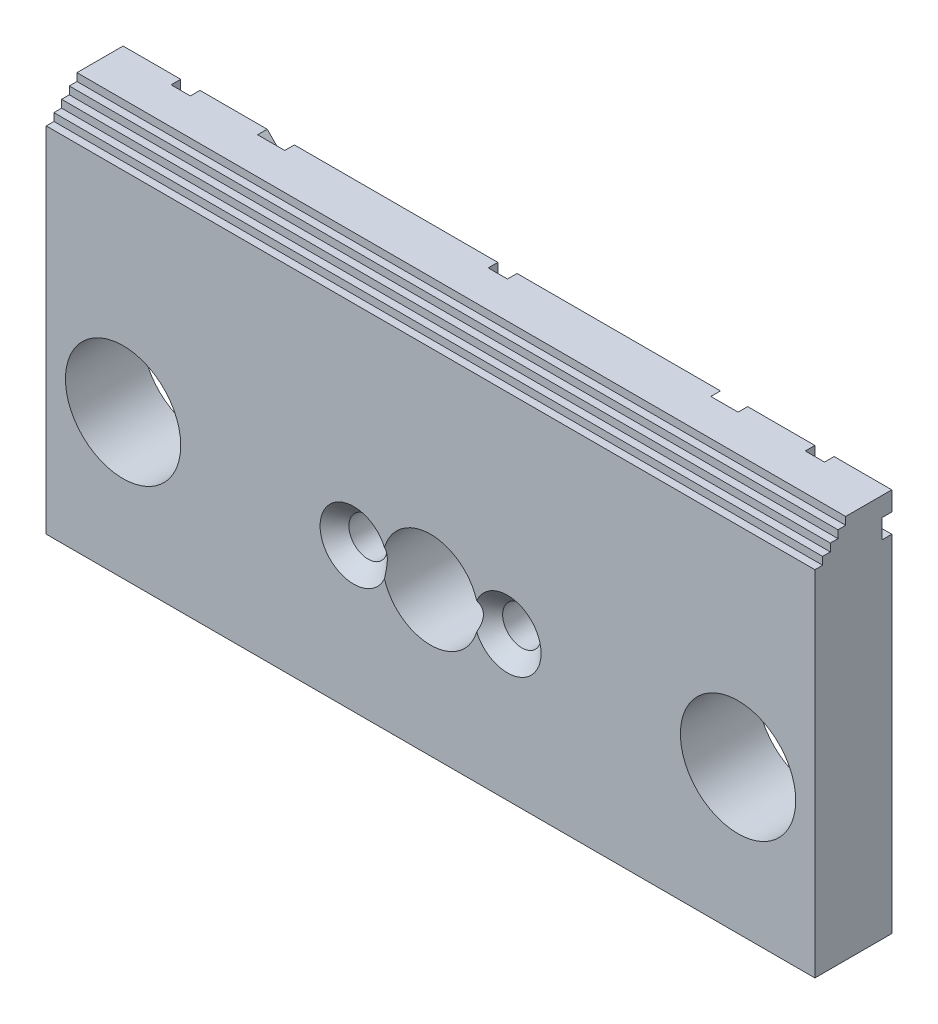
SolidWorks part; units mm, degrees
ref_plane "前视基准面" through (0, 0, 0) normal (0, 0, 1) x (1, 0, 0)
ref_plane "上视基准面" through (0, 0, 0) normal (0, 1, 0) x (1, 0, 0)
ref_plane "右视基准面" through (0, 0, 0) normal (1, 0, 0) x (0, 0, -1)
other "Configuration Table"
ref_plane "基准面1" through (0, 0, 1) normal (0, 0, -1) x (-1, 0, 0)
sketch "草图1" plane through (0, 0, 1) normal (0, 0, -1) x (-1, 0, 0)
  line L0 (-80, -13.3333) -> (0, -13.3333)
  line L1 (0, -13.3333) -> (0, 46.6667)
  line L2 (0, 46.6667) -> (-80, 46.6667)
  line L3 (-80, 46.6667) -> (-80, -13.3333)
  dimension "D1" = 80
  dimension "D2" = 60
extrude "凸台-拉伸1" add sketch "草图1" against normal blind 8
hole_wizard "Ø12.0 (12) 直径孔1" positions "草图21" profile "草图20" hole size "Ø12.0" standard "ANSI Metric" end condition through all
sketch "草图21" plane through (0, 0, 9) normal (0, 0, 1) x (1, 0, 0)
  line L0 (80, 21.6667) -> (0, 21.6667) construction
  line L1 (80, 46.6667) -> (80, -13.3333) construction
  line L2 (0, -13.3333) -> (0, 46.6667) construction
  line L3 (0, 46.6667) -> (80, 46.6667) construction
  point P0 (72, 21.6667)
  point P1 (8, 21.6667)
  dimension "D1" = 8
  dimension "D2" = 8
  dimension "D3" = 25
sketch "草图20" plane through (72, 21.6667, 9) normal (1, 0, 0) x (0, -1, 0)
  line L0 (0, 0) -> (0, 8)
  line L1 (0, 8) -> (6, 8)
  line L2 (6, 8) -> (6, 0)
  line L5 (6, 0) -> (0, 0)
  line L11 (0, -6.35) -> (0, 107.95) construction
  dimension "通孔孔直径" = 12
  dimension "通孔孔深度" = 8
hole_wizard "Ø10.0 (10) 直径孔2" positions "草图23" profile "草图22" hole size "Ø10.0" standard "ANSI Metric" end condition through all
sketch "草图23" plane through (0, 0, 1) normal (0, 0, -1) x (-1, 0, 0)
  line L0 (-80, 21.6667) -> (0, 21.6667) construction
  line L3 (0, 46.6667) -> (-80, 46.6667) construction
  point P0 (-40, 21.6667)
  dimension "D1" = 25
sketch "草图22" plane through (40, 21.6667, 1) normal (1, 0, 0) x (0, 1, 0)
  line L0 (0, 0) -> (0, 8)
  line L1 (0, 8) -> (5, 8)
  line L2 (5, 8) -> (5, 0)
  line L5 (5, 0) -> (0, 0)
  line L11 (0, -6.35) -> (0, 107.95) construction
  dimension "通孔孔直径" = 10
  dimension "通孔孔深度" = 8
hole_wizard "M3.5 平头机械螺钉的锥形沉头孔1" positions "草图25" profile "草图24" countersink size "M3.5" standard "ANSI Metric" end condition through all
sketch "草图25" plane through (0, 0, 9) normal (0, 0, 1) x (1, 0, 0)
  line L0 (0, 21.6667) -> (80, 21.6667) construction
  line L3 (0, 46.6667) -> (80, 46.6667) construction
  point P0 (32, 21.6667)
  point P1 (48, 21.6667)
  point P10 (40, 21.6667)
  dimension "D1" = 16
  dimension "D2" = 8
  dimension "D3" = 25
sketch "草图24" plane through (32, 21.6667, 9) normal (1, 0, 0) x (0, -1, 0)
  line L0 (0, 0) -> (0, 8)
  line L1 (0, 8) -> (2, 8)
  line L2 (2, 8) -> (2, 1.5)
  line L3 (2, 1.5) -> (3.5, 0)
  line L5 (3.5, 0) -> (0, 0)
  line L6 (-2, 1.5) -> (-3.5, 0) construction
  line L11 (0, -6.35) -> (0, 107.95) construction
  dimension "通孔孔直径" = 4
  dimension "通孔孔深度" = 8
  dimension "近端锥形沉头孔直径" = 7
  dimension "近端锥形沉头孔角度" = 90
sketch "草图27" plane through (0, 0, 1) normal (0, 0, -1) x (-1, 0, 0)
  line L0 (-40, 46.6667) -> (-40, -13.3333) construction
  line L1 (0, 46.6667) -> (-80, 46.6667) construction
  line L2 (-80, -13.3333) -> (0, -13.3333) construction
  line L3 (-80, 46.6667) -> (-80, -13.3333) construction
  line L4 (-80, 44.6667) -> (0, 44.6667)
  line L5 (-80, 44.6667) -> (-80, 42.6667)
  line L6 (-80, 42.6667) -> (0, 42.6667)
  line L7 (-40, 44.6667) -> (-40, 42.6667)
  line L8 (-80, 30.6667) -> (0, 30.6667) construction
  line L9 (-74, 46.6667) -> (-72, 46.6667)
  line L10 (-74, 46.6667) -> (-74, 30.6667)
  line L11 (-74, 30.6667) -> (-72, 30.6667)
  line L12 (-72, 46.6667) -> (-72, 30.6667)
  line L13 (-41, 46.6667) -> (-39, 46.6667)
  line L14 (-41, 46.6667) -> (-41, 30.6667)
  line L15 (-41, 30.6667) -> (-39, 30.6667)
  line L16 (-40, 46.6667) -> (-40, 30.6667)
  line L17 (0, -13.3333) -> (0, 46.6667) construction
  line L18 (-65, 46.6667) -> (-49, 30.6667)
  line L23 (-49, 30.6667) -> (-47.5858, 32.0809)
  line L24 (-47.5858, 32.0809) -> (-63.5858, 48.0809)
  line L25 (-63.5858, 48.0809) -> (-65, 46.6667)
  line L26 (-39, 46.6667) -> (-39, 30.6667)
  line L27 (-32.4142, 32.0809) -> (-16.4142, 48.0809)
  line L28 (-31, 30.6667) -> (-32.4142, 32.0809)
  line L29 (-15, 46.6667) -> (-31, 30.6667)
  line L30 (-16.4142, 48.0809) -> (-15, 46.6667)
  line L31 (-6, 30.6667) -> (-8, 30.6667)
  line L32 (-8, 46.6667) -> (-8, 30.6667)
  line L33 (-6, 46.6667) -> (-8, 46.6667)
  line L34 (-6, 46.6667) -> (-6, 30.6667)
  line L35 (0, 44.6667) -> (0, 42.6667)
  circle A0 centre (-73, 30.6667) radius 1
  circle A1 centre (-48.2929, 31.3738) radius 1
  circle A2 centre (-40, 30.6667) radius 1
  circle A3 centre (-31.7071, 31.3738) radius 1
  circle A4 centre (-7, 30.6667) radius 1
  line M27 (-80, 46.6667) -> (-80, -13.3333)
  line M29 (0, -13.3333) -> (0, 46.6667)
  dimension "D1" = 16
  dimension "D2" = 2
  dimension "D3" = 2
  dimension "D4" = 2
  dimension "D5" = 2
  dimension "D6" = 45
  dimension "D7" = 1
  dimension "D8" = 6
  dimension "D9" = 7
extrude "切除-拉伸1" cut sketch "草图27" against normal blind 1 contours L4 L34 L6 M29 | L32 L4 L29 L6 | L6 L27 L4 L26 | L24 L6 L14 L4 | L18 L4 L12 L6 | L10 L4 L6 M27 | A0 | A1 | A2 | A3 | A4
sketch "草图28" plane through (0, 0, 0) normal (-1, 0, 0) x (0, 0, 1)
  line L0 (9, 46.6667) -> (5.8, 46.6667)
  line L1 (9, 46.6667) -> (1, 46.6667) construction
  line L2 (5.8, 46.6667) -> (5.8, 45.8667)
  line L3 (5.8, 45.8667) -> (6.6, 45.8667)
  line L4 (6.6, 45.8667) -> (6.6, 45.0667)
  line L5 (6.6, 45.0667) -> (7.4, 45.0667)
  line L6 (7.4, 45.0667) -> (7.4, 44.2667)
  line L7 (7.4, 44.2667) -> (8.2, 44.2667)
  line L8 (8.2, 44.2667) -> (8.2, 43.4667)
  line L9 (8.2, 43.4667) -> (9, 43.4667)
  line L10 (9, -13.3333) -> (9, 46.6667) construction
  line L11 (9, 46.6667) -> (9, 43.4667)
  dimension "D1" = 0.8
  dimension "D2" = 0.8
  dimension "D3" = 0.8
  dimension "D4" = 0.8
  dimension "D5" = 0.8
  dimension "D6" = 0.8
  dimension "D7" = 0.8
  dimension "D8" = 0.8
extrude "切除-拉伸2" cut sketch "草图28" against normal up to next
sketch "草图29" plane through (0, 0, 1) normal (0, 0, -1) x (-1, 0, 0)
  line L0 (0, -13.3333) -> (0, 42.6667) construction
  line L1 (-80, -13.3333) -> (0, -13.3333)
  line L2 (-80, -13.3333) -> (-80, 6.6667)
  line L3 (-80, 6.6667) -> (0, 6.6667)
  line L4 (0, -13.3333) -> (0, 6.6667)
  dimension "D1" = 20
extrude "切除-拉伸3" cut sketch "草图29" against normal up to next
